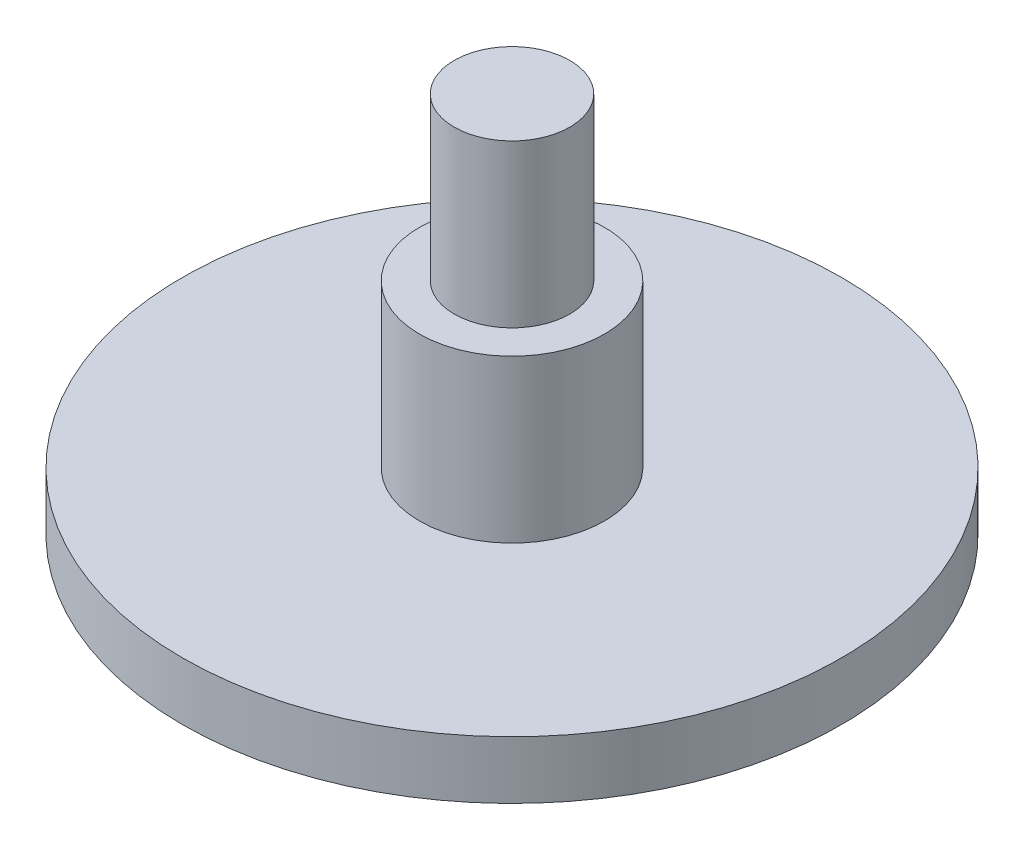
SolidWorks part; units mm, degrees
ref_plane "Front Plane" through (0, 0, 0) normal (0, 0, 1) x (1, 0, 0)
ref_plane "Top Plane" through (0, 0, 0) normal (0, 1, 0) x (1, 0, 0)
ref_plane "Right Plane" through (0, 0, 0) normal (1, 0, 0) x (0, 0, -1)
sketch "Sketch1" plane through (0, 0, 0) normal (0, 1, 0) x (1, 0, 0)
  circle A0 centre (0, 0) radius 28.5
extrude "Boss-Extrude1" add sketch "Sketch1" along normal blind 5
sketch "Sketch2" plane through (0, 5, 0) normal (0, 1, 0) x (1, 0, 0)
  circle A0 centre (0, 0) radius 8
extrude "Boss-Extrude2" add sketch "Sketch2" along normal blind 14
sketch "Sketch3" plane through (0, 19, 0) normal (0, 1, 0) x (1, 0, 0)
  circle A0 centre (0, 0) radius 5
extrude "Boss-Extrude3" add sketch "Sketch3" along normal blind 14
